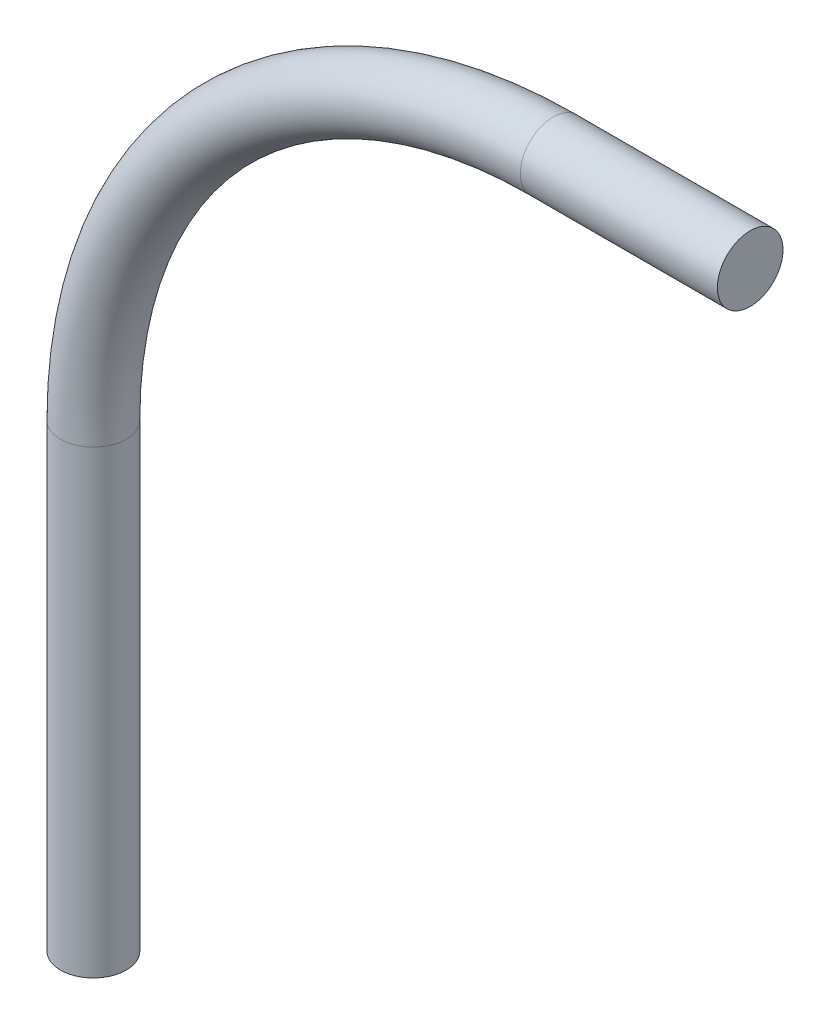
SolidWorks part; units mm, degrees
ref_plane "Front Plane" through (0, 0, 0) normal (0, 0, 1) x (1, 0, 0)
ref_plane "Top Plane" through (0, 0, 0) normal (0, 1, 0) x (1, 0, 0)
ref_plane "Right Plane" through (0, 0, 0) normal (1, 0, 0) x (0, 0, -1)
sketch "Sketch1" plane through (0, 0, 0) normal (0, 0, 1) x (1, 0, 0)
  line L0 (0, 0) -> (0, 35)
  line L1 (35, 70) -> (50, 70)
  arc A0 (35, 70) -> (0, 35) centre (35, 35) ccw
  dimension "D3" = 70
sketch "Sketch3" plane through (0, 0, 0) normal (0, 1, 0) x (1, 0, 0)
  circle A0 centre (0, 0) radius 2.5
sweep "Sweep2" add profiles "Sketch3" path "Sketch1"
